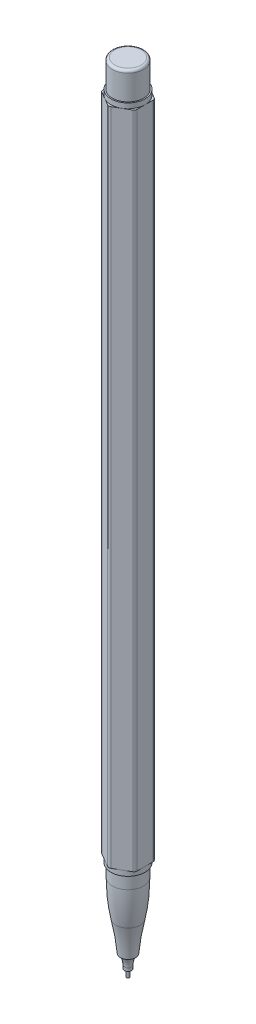
SolidWorks part; units mm, degrees
ref_plane "Plano frontal" through (0, 0, 0) normal (0, 0, 1) x (1, 0, 0)
ref_plane "Plano superior" through (0, 0, 0) normal (0, 1, 0) x (1, 0, 0)
ref_plane "Plano direito" through (0, 0, 0) normal (1, 0, 0) x (0, 0, -1)
sketch "Esboço1" plane through (0, 0, 0) normal (0, 1, 0) x (1, 0, 0)
  line L1 (0.3, -3.695) -> (3.05, -2.1073)
  line L2 (3.35, -1.5877) -> (3.35, 1.5877)
  line L3 (3.05, 2.1073) -> (0.3, 3.695)
  line L4 (-0.3, 3.695) -> (-3.05, 2.1073)
  line L5 (-3.35, 1.5877) -> (-3.35, -1.5877)
  line L6 (-3.05, -2.1073) -> (-0.3, -3.695)
  circle A0 centre (0, 0) radius 3.35 construction
  arc A1 (-3.35, -1.5877) -> (-3.05, -2.1073) centre (-2.75, -1.5877) ccw
  arc A2 (0.3, -3.695) -> (-0.3, -3.695) centre (0, -3.1754) cw
  arc A3 (3.05, -2.1073) -> (3.35, -1.5877) centre (2.75, -1.5877) ccw
  arc A4 (3.35, 1.5877) -> (3.05, 2.1073) centre (2.75, 1.5877) ccw
  arc A5 (-3.05, 2.1073) -> (-3.35, 1.5877) centre (-2.75, 1.5877) ccw
  arc A6 (0.3, 3.695) -> (-0.3, 3.695) centre (0, 3.1754) ccw
  dimension "D2" = 0.6
  dimension "D1" = 6.7
extrude "Ressalto-extrusão1" add sketch "Esboço1" along normal blind 130
sketch "Esboço2" plane through (0, 130, 0) normal (0, 1, 0) x (1, 0, 0)
  line L0 (-0.3, 3.695) -> (-3.05, 2.1073) construction
  circle A0 centre (0, 0) radius 3.35
extrude "Ressalto-extrusão2" add sketch "Esboço2" along normal blind 1
sketch "Esboço3" plane through (0, 131, 0) normal (0, 1, 0) x (1, 0, 0)
  circle A0 centre (0, 0) radius 3.1
  dimension "D1" = 6.2
extrude "Ressalto-extrusão3" add sketch "Esboço3" along normal blind 5.4
fillet "Filete1" radius 0.5 1 edges at (0, 136.4, 3.1)
sketch "Esboço4" plane through (0, 0, 0) normal (0, -1, 0) x (1, 0, 0)
  circle A0 centre (0, 0) radius 3.35
extrude "Ressalto-extrusão4" add sketch "Esboço4" along normal blind 1
sketch "Esboço5" plane through (0, 0, 0) normal (0, 0, 1) x (1, 0, 0)
  line L0 (0, -1) -> (0, -20.5) construction
  line L1 (-3.35, -1) -> (3.35, -1) construction
  line L2 (3.05, -1) -> (3.05, -3.5)
  line L3 (0, -20.5) -> (0.3, -20.5)
  line L4 (0.3, -20.5) -> (0.3, -19.1)
  line L5 (0.3, -19.1) -> (0.7, -19.1)
  line L6 (0.7, -19.1) -> (0.7, -18.5)
  line L7 (1.5, -16.5) -> (1.2, -16.5)
  line L8 (0, -1) -> (3.05, -1)
  line L9 (0, -1) -> (0, -20.5)
  arc A0 (3.05, -3.5) -> (2.3882, -10.5) centre (-34.3013, -3.5) cw
  arc A1 (2.3882, -10.5) -> (1.5, -16.5) centre (44.4582, -19.7935) ccw
  arc A2 (0.7, -18.5) -> (1.2, -16.5) centre (5.5054, -18.6388) cw
  dimension "D1" = 19.5
  dimension "D2" = 3.05
  dimension "D3" = 2.5
  dimension "D4" = 7
  dimension "D5" = 6
  dimension "D6" = 0.3
  dimension "D7" = 0.7
  dimension "D8" = 0.5
  dimension "D9" = 0.3
  dimension "D10" = 2
  dimension "D11" = 1.4
revolve "Revolução1" add sketch "Esboço5" angle 360 about L0
